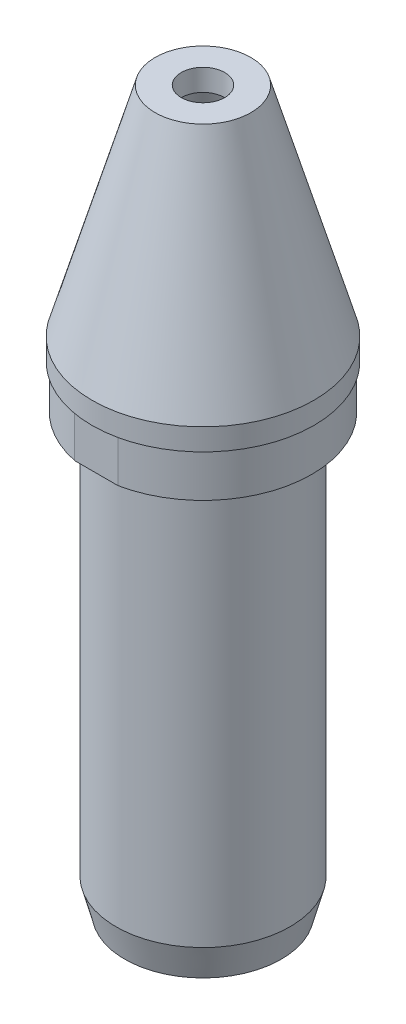
SolidWorks part; units mm, degrees
ref_plane "Alzado" through (0, 0, 0) normal (0, 0, 1) x (1, 0, 0)
ref_plane "Planta" through (0, 0, 0) normal (0, 1, 0) x (1, 0, 0)
ref_plane "Vista lateral" through (0, 0, 0) normal (1, 0, 0) x (0, 0, -1)
sketch "Croquis1" plane through (0, 0, 0) normal (0, 0, 1) x (1, 0, 0)
  line L0 (1.8, 10) -> (1.8, 0)
  line L1 (2, 0) -> (2, 10)
  line L2 (2, 10) -> (2.5, 10)
  line L3 (2.5, 10) -> (2.5, 11)
  line L4 (2.5, 11) -> (2.55, 11)
  line L5 (1.1, 16.5) -> (0.5, 16.5)
  line L6 (0, 0) -> (0, 10.356) construction
  line L7 (2.55, 11) -> (2.55, 11.5)
  line L8 (2.55, 11.5) -> (1.1, 16.5)
  line L9 (1.8, 0) -> (2, 0)
  line L10 (1.5, 10.5) -> (1.05, 10.5)
  line L11 (1.5, 10.5) -> (2, 10.5)
  line L12 (2, 10.5) -> (2, 11.5)
  line L13 (0.7244, 16) -> (2, 11.5)
  line L14 (1.05, 10.5) -> (1.05, 10)
  line L15 (1.05, 10) -> (1.8, 10)
  line L16 (0.7244, 16) -> (0.5, 16)
  line L17 (2.0294, 11.5) -> (0.7244, 16) construction
  line L18 (2, 11.5) -> (2.0294, 11.5) construction
  line L19 (2.0294, 11.5) -> (2.0294, 11.5) construction
  line L20 (0, 0.5) -> (1.5, 0.5) construction
  line L21 (0, 0) -> (2, 0) construction
  line L22 (1.5, 0.5) -> (1.5, 10.5) construction
  line L23 (0.5, 16) -> (0.5, 16.5)
  line L24 (0.7244, 16) -> (0, 16) construction
  line L25 (1.1, 16.5) -> (0, 16.5) construction
  line L26 (1.8, 0) -> (2, 0.7464)
  dimension "D2" = 10
  dimension "D3" = 1
  dimension "D4" = 0.5
  dimension "D5" = 0.05
  dimension "D6" = 0.5
  dimension "D7" = 5
  dimension "D9" = 0.75
  dimension "D10" = 0.5
  dimension "D11" = 75
  dimension "D12" = 1.8
  dimension "D13" = 2
  dimension "D14" = 1.1
  dimension "D8" = 0.5
revolve "Revolución1" add sketch "Croquis1" angle 360 about L6
sketch "Croquis2" plane through (0, 10, 0) normal (0, -1, 0) x (1, 0, 0)
  line L0 (0, 0) -> (3.5343, 0) construction
  line L1 (-2.5, 2.55) -> (2.5, 2.55)
  line L2 (-2.5, 2.55) -> (-2.5, 2.45)
  line L3 (-2.5, 2.45) -> (2.5, 2.45)
  line L4 (2.5, 2.55) -> (2.5, 2.45)
  line L5 (-2.5, 2.55) -> (2.5, 2.45) construction
  line L6 (-2.5, 2.45) -> (2.5, 2.55) construction
  line L7 (-2.5, -2.45) -> (2.5, -2.55) construction
  line L8 (-2.5, -2.55) -> (2.5, -2.45) construction
  line L9 (2.5, -2.55) -> (2.5, -2.45)
  line L10 (-2.5, -2.45) -> (2.5, -2.45)
  line L11 (-2.5, -2.55) -> (-2.5, -2.45)
  line L12 (-2.5, -2.55) -> (2.5, -2.55)
  circle A0 centre (0, 0) radius 2.5 construction
  circle A1 centre (0, 0) radius 2.5 construction
  point P0 (0, 2.5)
  point P16 (0, -2.5)
  dimension "D1" = 0.1
extrude "Cortar-Extruir1" cut sketch "Croquis2" against normal blind 1
